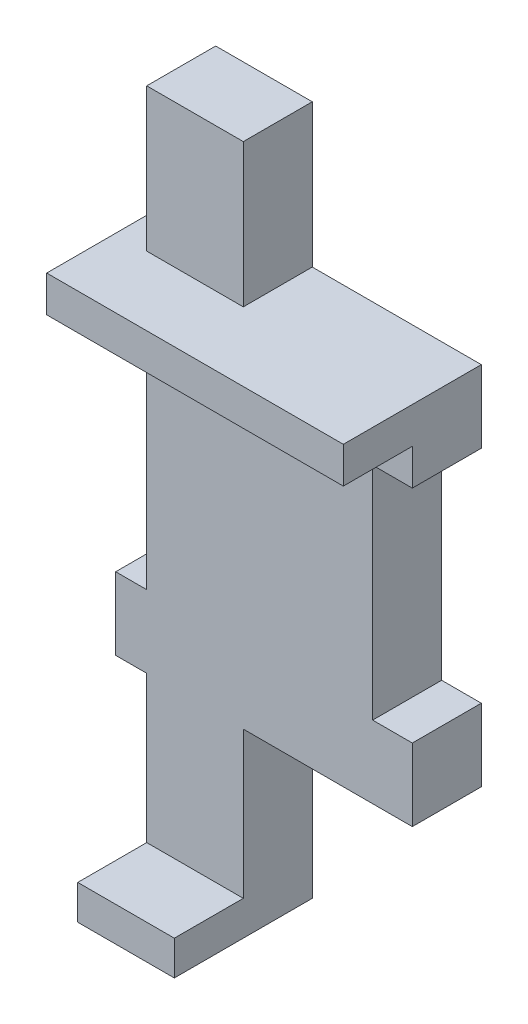
SolidWorks part; units mm, degrees
ref_plane "Front Plane" through (0, 0, 0) normal (0, 0, 1) x (1, 0, 0)
ref_plane "Top Plane" through (0, 0, 0) normal (0, 1, 0) x (1, 0, 0)
ref_plane "Right Plane" through (0, 0, 0) normal (1, 0, 0) x (0, 0, -1)
sketch "Sketch1" plane through (0, 0, 0) normal (0, 0, 1) x (1, 0, 0)
  line L1 (-2.8, -20) -> (2.8, -20)
  line L2 (-2.8, -20) -> (-2.8, 20)
  line L3 (-2.8, 20) -> (2.8, 20)
  line L4 (2.8, -20) -> (2.8, 20)
  line L5 (-2.8, -20) -> (2.8, 20) construction
  line L6 (-2.8, 20) -> (2.8, -20) construction
  point P0 (0, 0)
  dimension "D1" = 40
  dimension "D2" = 5.6
extrude "Boss-Extrude1" add sketch "Sketch1" along normal blind 4 contours L4 L3 L2 L1
sketch "Sketch2" plane through (0, 0, 4) normal (0, 0, 1) x (1, 0, 0)
  line L0 (2.8, -20) -> (2.8, 20) construction
  line L1 (-2.8, -20) -> (2.8, -20)
  line L2 (-2.8, -20) -> (-2.8, -18)
  line L3 (-2.8, -18) -> (2.8, -18)
  line L4 (2.8, -20) -> (2.8, -18)
  dimension "D1" = 2
extrude "Boss-Extrude2" add sketch "Sketch2" along normal blind 4
sketch "Sketch4" plane through (-2.8, 0, 0) normal (-1, 0, 0) x (0, 0, 1)
  line L0 (0, -20) -> (0, 20) construction
  line L1 (0, 11.7) -> (4, 11.7)
  line L2 (0, 11.7) -> (0, 7.5)
  line L3 (0, 7.5) -> (4, 7.5)
  line L4 (4, 11.7) -> (4, 7.5)
  line L5 (4, -18) -> (4, 20) construction
  line L6 (8, -20) -> (0, -20) construction
  dimension "D1" = 4.2
  dimension "D2" = 27.5
extrude "Boss-Extrude3" add sketch "Sketch4" along normal blind 1.8
ref_plane "Plane1" through (0, 0, 0) normal (-1, 0, 0) x (0, 0, 1)
mirror "Mirror1" about plane through (0, 0, 0) normal (-1, 0, 0) of "Boss-Extrude3"
sketch "Sketch6" plane through (0, 0, 4) normal (0, 0, 1) x (1, 0, 0)
  line L0 (2.8, 1.1) -> (-2.8, 1.1) construction
  line L1 (2.8, -18) -> (2.8, 7.5) construction
  line L2 (-2.8, -18) -> (-2.8, 7.5) construction
  line L3 (2.8, -18) -> (-2.8, -18) construction
  line L4 (4.6, 7.5) -> (2.8, 7.5) construction
  dimension "D1" = 19.1
  dimension "D2" = 6.4
sketch "Sketch7" plane through (-2.8, 0, 0) normal (-1, 0, 0) x (0, 0, 1)
  line L0 (4, 1.1) -> (0, 1.1) construction
  line L1 (4, -18) -> (4, 7.5) construction
  line L2 (0, -20) -> (0, 7.5) construction
  line L3 (8, -18) -> (4, -18) construction
  dimension "D1" = 19.1
ref_plane "Plane3" through (0, 1.1, 0) normal (0, -1, 0) x (-1, 0, 0)
mirror "Mirror2" about plane through (0, 1.1, 0) normal (0, -1, 0) of "Mirror1", "Boss-Extrude3"
sketch "Sketch8" plane through (4.6, 0, 0) normal (1, 0, 0) x (0, 0, -1)
  line L1 (-4, 11.7) -> (0, 11.7)
  line L2 (-4, 11.7) -> (-4, 7.5)
  line L3 (-4, 7.5) -> (0, 7.5)
  line L4 (0, 11.7) -> (0, 7.5)
  line L5 (-4, -5.3) -> (0, -5.3)
  line L6 (-4, -5.3) -> (-4, -9.5)
  line L7 (-4, -9.5) -> (0, -9.5)
  line L8 (0, -5.3) -> (0, -9.5)
extrude "Boss-Extrude4" add sketch "Sketch8" along normal blind 8
sketch "Sketch9" plane through (0, 0, 4) normal (0, 0, 1) x (1, 0, 0)
  line L0 (12.6, 11.7) -> (12.6, 7.5) construction
  line L1 (-4.6, 11.7) -> (12.6, 11.7)
  line L2 (-4.6, 11.7) -> (-4.6, 9.6)
  line L3 (-4.6, 9.6) -> (12.6, 9.6)
  line L4 (12.6, 11.7) -> (12.6, 9.6)
extrude "Boss-Extrude5" add sketch "Sketch9" along normal blind 4
sketch "Sketch10" plane through (2.8, 0, 0) normal (1, 0, 0) x (0, 0, -1)
  line L1 (-4, 7.5) -> (0, 7.5)
  line L2 (-4, 7.5) -> (-4, -5.3)
  line L3 (-4, -5.3) -> (0, -5.3)
  line L4 (0, 7.5) -> (0, -5.3)
extrude "Boss-Extrude6" add sketch "Sketch10" along normal blind 7.5
sketch "Sketch11" plane through (0, 0, 0) normal (0, 0, -1) x (-1, 0, 0)
  line L0 (2.8, -20) -> (-2.8, -20) construction
  line L3 (2.8, -5.3) -> (2.8, 7.5) construction
  circle A0 centre (-4.9, 1.1) radius 1.5
  dimension "D1" = 3
  dimension "D2" = 21.1
  dimension "D3" = 7.7
extrude "Cut-Extrude1" cut sketch "Sketch11" against normal blind 1
